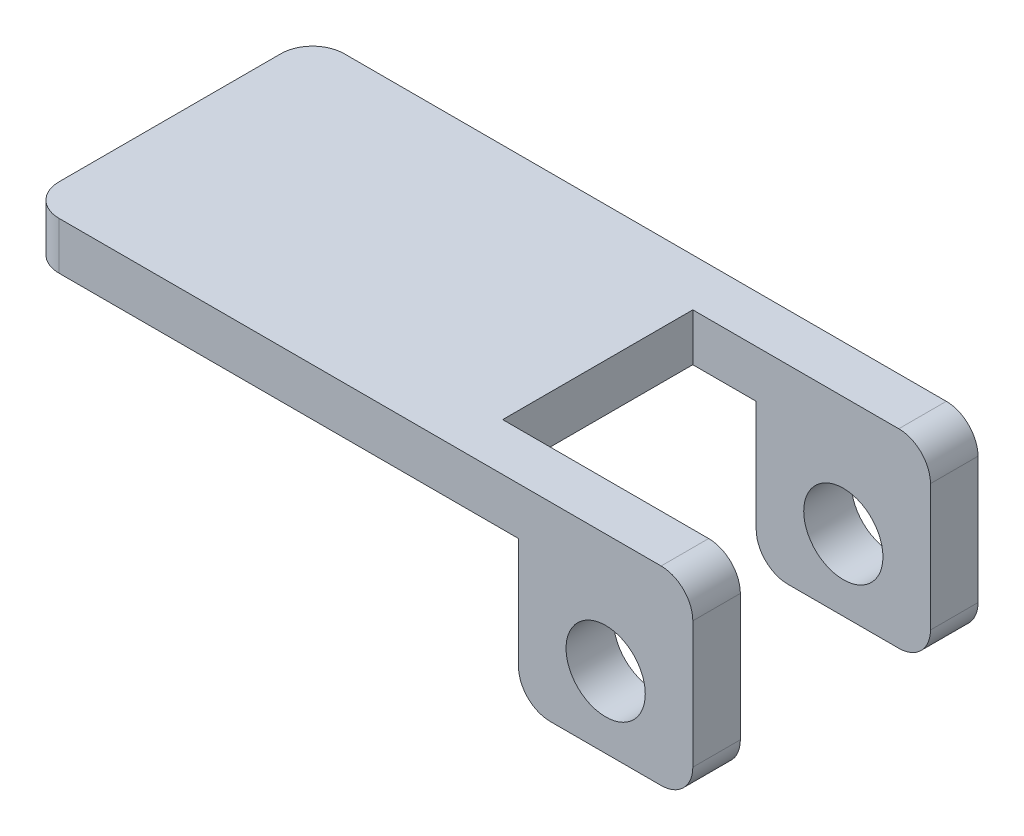
SolidWorks part; units mm, degrees
ref_plane "Front Plane" through (0, 0, 0) normal (0, 0, 1) x (1, 0, 0)
ref_plane "Top Plane" through (0, 0, 0) normal (0, 1, 0) x (1, 0, 0)
ref_plane "Right Plane" through (0, 0, 0) normal (1, 0, 0) x (0, 0, -1)
sketch "Sketch1" plane through (0, 0, 0) normal (0, 1, 0) x (1, 0, 0)
  line L1 (0, 0) -> (42, 0)
  line L2 (0, 0) -> (0, 18)
  line L3 (0, 18) -> (42, 18)
  line L4 (42, 0) -> (42, 18)
  dimension "D1" = 18
  dimension "D2" = 42
extrude "Boss-Extrude1" add sketch "Sketch1" along normal blind 3
sketch "Sketch2" plane through (0, 0, 0) normal (0, -1, 0) x (1, 0, 0)
  line L1 (42, 0) -> (31, 0)
  line L2 (42, 0) -> (42, -3)
  line L3 (42, -3) -> (31, -3)
  line L4 (31, 0) -> (31, -3)
  line L5 (42, -18) -> (31, -18)
  line L6 (42, -18) -> (42, -15)
  line L7 (42, -15) -> (31, -15)
  line L8 (31, -18) -> (31, -15)
  dimension "D1" = 3
  dimension "D2" = 3
  dimension "D3" = 11
  dimension "D4" = 11
extrude "Boss-Extrude2" add sketch "Sketch2" along normal blind 9
sketch "Sketch3" plane through (0, 0, 0) normal (0, 0, 1) x (1, 0, 0)
  line L0 (31, 0) -> (42, 0) construction
  line L1 (42, 3) -> (42, -9) construction
  line L2 (31, -4.5) -> (42, -4.5) construction
  line L3 (31, -9) -> (31, 0) construction
  line L4 (36.5, 0) -> (36.5, -9) construction
  line L5 (42, -9) -> (31, -9) construction
  circle A0 centre (36.5, -4.5) radius 2.5
  dimension "D1" = 5
extrude "Cut-Extrude1" cut sketch "Sketch3" against normal through all
sketch "Sketch4" plane through (0, 3, 0) normal (0, 1, 0) x (1, 0, 0)
  line L0 (42, 0) -> (42, 18) construction
  line L1 (42, 15) -> (27, 15)
  line L2 (42, 15) -> (42, 3)
  line L3 (42, 3) -> (27, 3)
  line L4 (27, 15) -> (27, 3)
  line L5 (42, 18) -> (0, 18) construction
  line L6 (0, 0) -> (42, 0) construction
  dimension "D1" = 3
  dimension "D2" = 3
  dimension "D3" = 15
extrude "Cut-Extrude2" cut sketch "Sketch4" against normal blind 3
fillet "Fillet1" radius 2 2 edges at (0, 1.5, -18) (0, 1.5, 0)
fillet "Fillet2" radius 2 6 edges at (42, 3, -1.5) (42, -9, -1.5) (31, -9, -1.5) (42, -9, -16.5) (31, -9, -16.5) (42, 3, -16.5)
